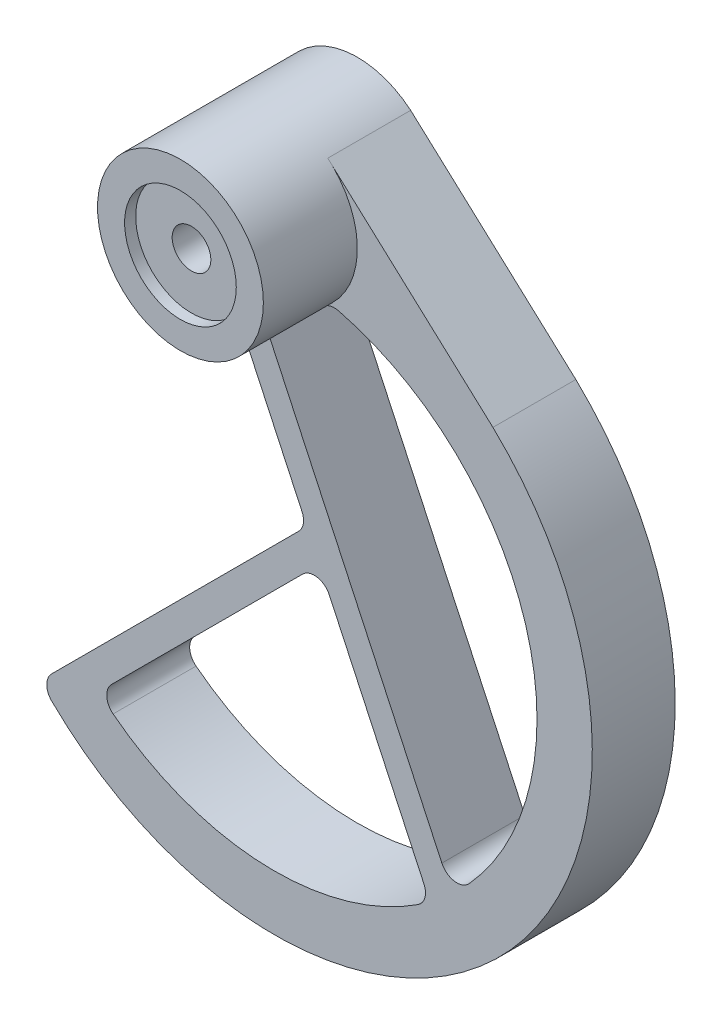
SolidWorks part; units mm, degrees
material "ABS"
ref_plane "正面" through (0, 0, 0) normal (0, 0, 1) x (1, 0, 0)
ref_plane "平面" through (0, 0, 0) normal (0, 1, 0) x (1, 0, 0)
ref_plane "右側面" through (0, 0, 0) normal (1, 0, 0) x (0, 0, -1)
sketch "ｽｹｯﾁ1" plane through (0, 0, 0) normal (0, 0, 1) x (1, 0, 0)
  line L1 (9.9336, 0.7043) -> (27.0462, -35.9938)
  line L2 (9.6418, 68.9907) -> (39.5241, 41.7624)
  line L4 (4.3888, 7.9244) -> (-40.3035, -36.7679)
  line L5 (5.0933, 1.5578) -> (-29.4572, -32.9928)
  line L6 (-13.5946, 51.1607) -> (4.9864, 11.3135)
  line L7 (30.2877, -31.1143) -> (-2.0547, 38.2444)
  arc A0 (-40.2839, -41.0299) -> (37.9168, 43.2269) centre (0, 0) ccw
  arc A1 (-29.1788, -37.4813) -> (25.9673, -39.7737) centre (0, 0) ccw
  arc A2 (0.5535, 42.5102) -> (9.0577, 45.5435) centre (0, 57.5) ccw
  arc A3 (35.2318, -31.8586) -> (11.602, 46.0613) centre (0, 0) ccw
  arc A4 (10.5469, 68.1659) -> (-13.5946, 51.1607) centre (0, 57.5) ccw
  arc A5 (-40.3035, -36.7679) -> (-40.2839, -41.0299) centre (-38.1821, -38.8893) ccw
  arc A6 (-29.4572, -32.9928) -> (-29.1788, -37.4813) centre (-27.3359, -35.1141) ccw
  arc A7 (27.0462, -35.9938) -> (25.9673, -39.7737) centre (24.3273, -37.2617) cw
  arc A8 (5.0933, 1.5578) -> (9.9336, 0.7043) centre (7.2147, -0.5635) cw
  arc A9 (35.2318, -31.8586) -> (30.2877, -31.1143) centre (33.0067, -29.8464) cw
  arc A10 (4.9864, 11.3135) -> (4.3888, 7.9244) centre (2.2675, 10.0457) cw
  arc A11 (-2.0547, 38.2444) -> (0.5535, 42.5102) centre (0.6642, 39.5123) cw
  arc A12 (11.602, 46.0613) -> (9.0577, 45.5435) centre (10.8692, 43.1522) ccw
  point P24 (8.1229, 4.5874)
  dimension "D1" = 3
  dimension "D2" = 3
  dimension "D3" = 3
  dimension "D4" = 3
  dimension "D5" = 3
  dimension "D6" = 3
  dimension "D7" = 3
  dimension "D8" = 3
extrude "ﾎﾞｽ - 押し出し1" add sketch "ｽｹｯﾁ1" along normal blind 15 contours L6 A10 L4 A5 A0 L2 A4 A12 A3 A9 L7 A11 A2 L5 A8 L1 A7 A1 A6
sketch "ｽｹｯﾁ6" plane through (0, 0, 15) normal (0, 0, 1) x (1, 0, 0)
  circle A0 centre (0, 57.5) radius 3.5
extrude "ｶｯﾄ - 押し出し2" cut sketch "ｽｹｯﾁ6" against normal blind 15
sketch "ｽｹｯﾁ9" plane through (0, 0, 15) normal (0, 0, 1) x (1, 0, 0)
  circle A0 centre (0, 57.5) radius 15
  circle A1 centre (0, 57.5) radius 3.5
extrude "ﾎﾞｽ - 押し出し2" add sketch "ｽｹｯﾁ9" along normal blind 17
sketch "ｽｹｯﾁ10" plane through (0, 0, 32) normal (0, 0, 1) x (1, 0, 0)
  circle A0 centre (0, 57.5) radius 10.1
extrude "ｶｯﾄ - 押し出し5" cut sketch "ｽｹｯﾁ10" against normal blind 2
